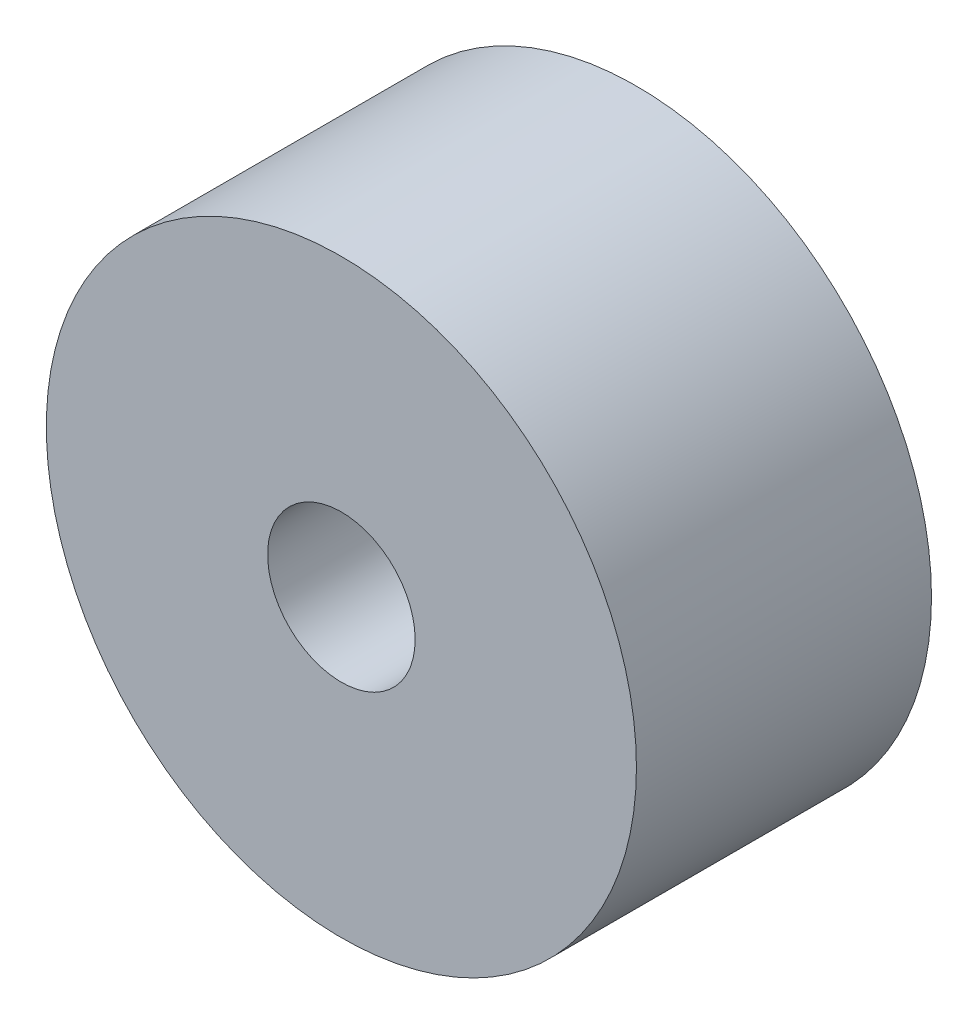
SolidWorks part; units mm, degrees
ref_plane "Front Plane" through (0, 0, 0) normal (0, 0, 1) x (1, 0, 0)
ref_plane "Top Plane" through (0, 0, 0) normal (0, 1, 0) x (1, 0, 0)
ref_plane "Right Plane" through (0, 0, 0) normal (1, 0, 0) x (0, 0, -1)
sketch "Sketch1" plane through (0, 0, 0) normal (0, 0, 1) x (1, 0, 0)
  circle A0 centre (0, 0) radius 2.5
  circle A1 centre (0, 0) radius 10
extrude "Boss-Extrude1" add sketch "Sketch1" along normal mid plane 10
